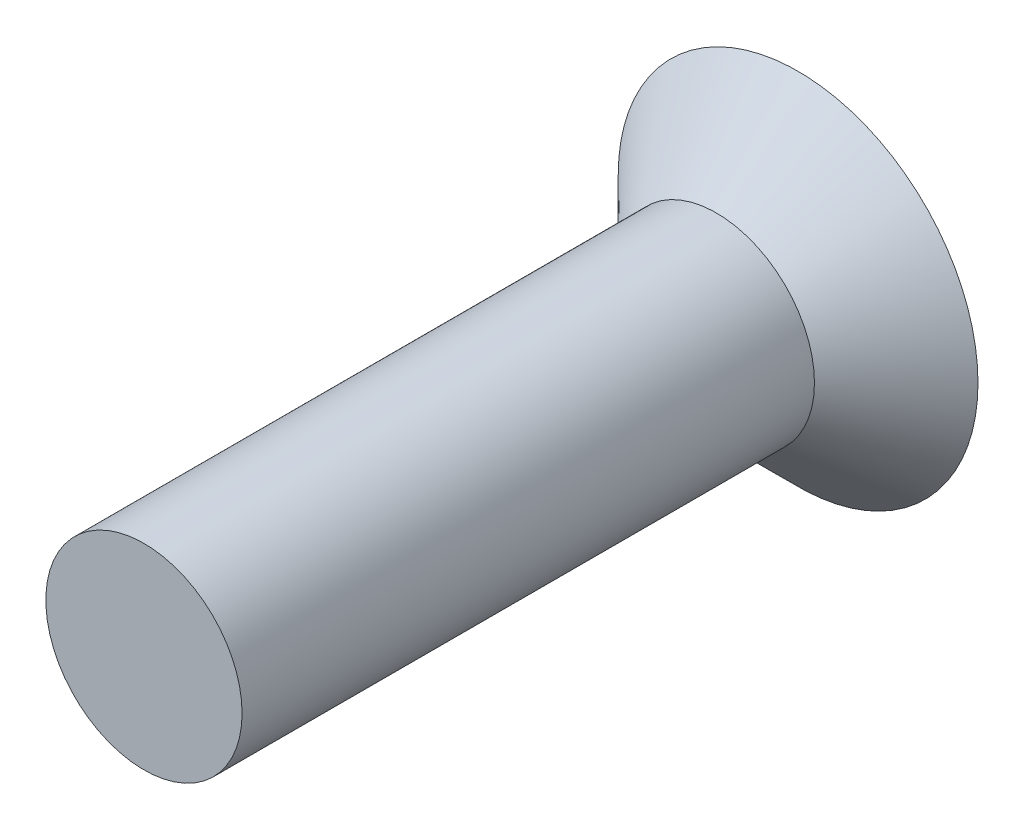
SolidWorks part; units mm, degrees
ref_plane "前视基准面" through (0, 0, 0) normal (0, 0, 1) x (1, 0, 0)
ref_plane "上视基准面" through (0, 0, 0) normal (0, 1, 0) x (1, 0, 0)
ref_plane "右视基准面" through (0, 0, 0) normal (1, 0, 0) x (0, 0, -1)
other "Configuration Table"
sketch "草图1" plane through (0, 0, 0) normal (0, 0, 1) x (1, 0, 0)
  circle A1 centre (0, 0) radius 1.5
extrude "M3简化螺杆_沉头总长55mm" add sketch "草图1" along normal blind 8.75 from offset 1.25
sketch "草图2" plane through (0, 0, 0) normal (0, 0, 1) x (1, 0, 0)
  circle A0 centre (0, 0) radius 2.75
extrude "M3沉头_D5p5_90度" add sketch "草图2" along normal blind 1.25 draft 45
